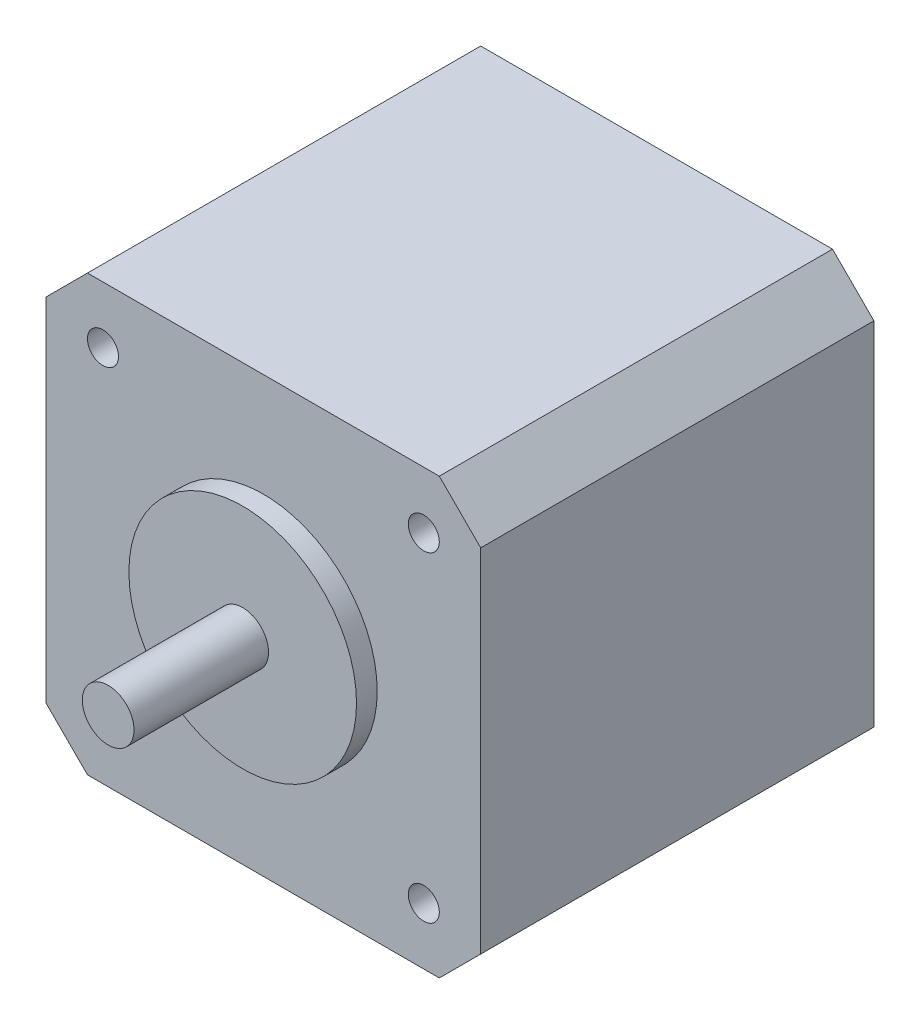
SolidWorks part; units mm, degrees
ref_plane "Alzado" through (0, 0, 0) normal (0, 0, 1) x (1, 0, 0)
ref_plane "Planta" through (0, 0, 0) normal (0, 1, 0) x (1, 0, 0)
ref_plane "Vista lateral" through (0, 0, 0) normal (1, 0, 0) x (0, 0, -1)
sketch "Croquis1" plane through (0, 0, 0) normal (0, 0, 1) x (1, 0, 0)
  line L1 (-21, 21) -> (21, 21)
  line L2 (-21, 21) -> (-21, -21)
  line L3 (-21, -21) -> (21, -21)
  line L4 (21, 21) -> (21, -21)
  line L5 (-21, 21) -> (21, -21) construction
  line L6 (-21, -21) -> (21, 21) construction
  point P0 (0, 0)
  dimension "D1" = 42
  dimension "D2" = 42
extrude "Saliente-Extruir1" add sketch "Croquis1" along normal blind 38
sketch "Croquis2" plane through (0, 0, 38) normal (0, 0, 1) x (1, 0, 0)
  circle A0 centre (0, 0) radius 11
  dimension "D1" = 22
extrude "Saliente-Extruir2" add sketch "Croquis2" along normal blind 2
sketch "Croquis3" plane through (0, 0, 40) normal (0, 0, 1) x (1, 0, 0)
  circle A0 centre (0, 0) radius 2.5
  dimension "D1" = 5
extrude "Saliente-Extruir3" add sketch "Croquis3" along normal blind 13
chamfer "Chaflán1" distance 4 angle 45 4 edges at (-21, -21, 19) (-21, 21, 19) (21, -21, 19) (21, 21, 19)
sketch "Croquis4" plane through (0, 0, 38) normal (0, 0, 1) x (1, 0, 0)
  line L1 (-15.5, 15.5) -> (15.5, 15.5) construction
  line L2 (-15.5, 15.5) -> (-15.5, -15.5) construction
  line L3 (-15.5, -15.5) -> (15.5, -15.5) construction
  line L4 (15.5, 15.5) -> (15.5, -15.5) construction
  line L5 (-15.5, 15.5) -> (15.5, -15.5) construction
  line L6 (-15.5, -15.5) -> (15.5, 15.5) construction
  circle A0 centre (15.5, 15.5) radius 1.5
  circle A1 centre (-15.5, 15.5) radius 1.5
  circle A2 centre (-15.5, -15.5) radius 1.5
  circle A3 centre (15.5, -15.5) radius 1.5
  point P0 (0, 0)
  dimension "D3" = 3
  dimension "D4" = 3
  dimension "D5" = 3
  dimension "D6" = 3
  dimension "D1" = 31
  dimension "D2" = 31
extrude "Cortar-Extruir1" cut sketch "Croquis4" against normal through all
sketch "Croquis5" plane through (0, 21, 0) normal (0, 1, 0) x (1, 0, 0)
  text T0 "FRONT" font "Arial" height 5
sketch "Croquis6" plane through (0, -21, 0) normal (0, -1, 0) x (1, 0, 0)
  line L0 (1.3531, 3.7745) -> (-1.3531, 3.7745) construction
  line L1 (1.3531, 3.1136) -> (-1.3531, 3.1136)
  line L2 (1.3531, 4.4354) -> (-1.3531, 4.4354)
  arc A0 (1.3531, 3.1136) -> (1.3531, 4.4354) centre (1.3531, 3.7745) ccw
  arc A1 (-1.3531, 4.4354) -> (-1.3531, 3.1136) centre (-1.3531, 3.7745) ccw
  point P2 (0, 3.7745)
extrude "Saliente-Extruir4" add sketch "Croquis6" along normal blind 3
